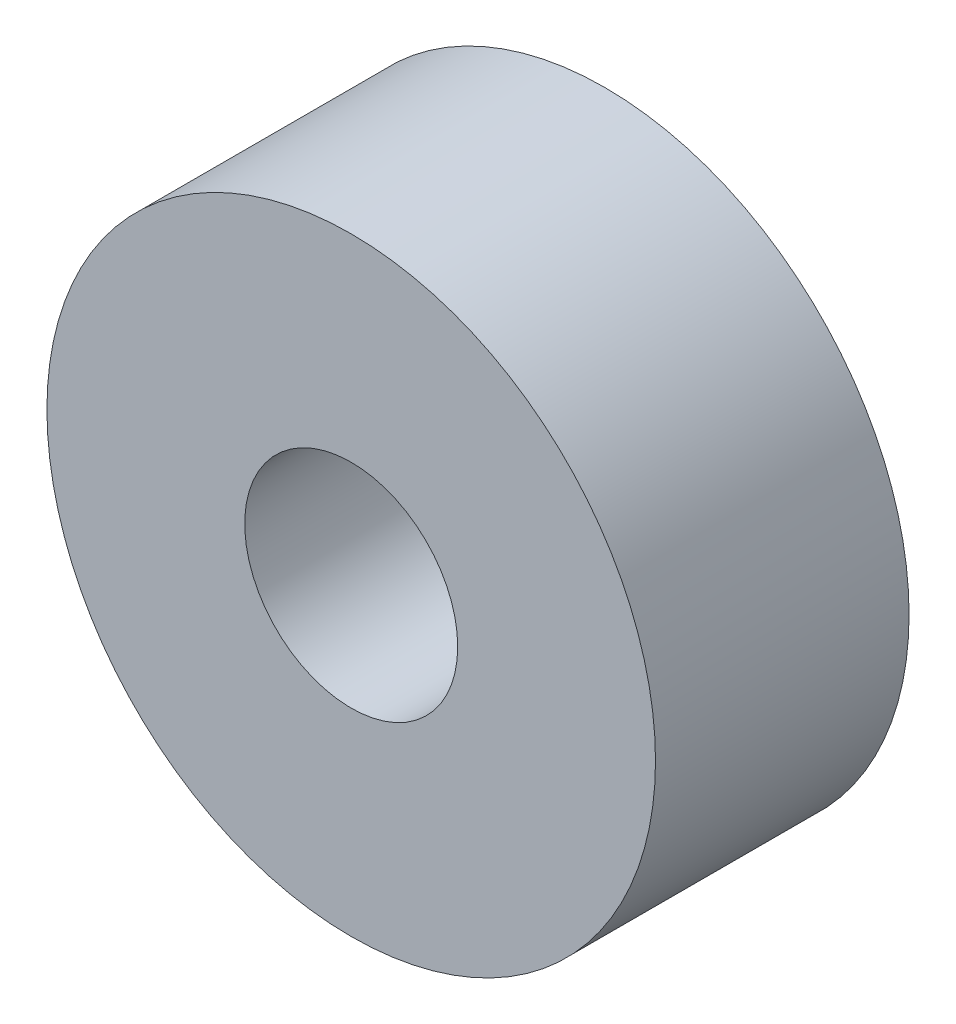
SolidWorks part; units mm, degrees
ref_plane "Front Plane" through (0, 0, 0) normal (0, 0, 1) x (1, 0, 0)
ref_plane "Top Plane" through (0, 0, 0) normal (0, 1, 0) x (1, 0, 0)
ref_plane "Right Plane" through (0, 0, 0) normal (1, 0, 0) x (0, 0, -1)
sketch "Sketch1" plane through (0, 0, 0) normal (0, 0, 1) x (1, 0, 0)
  circle A0 centre (0, 0) radius 6
  circle A1 centre (0, 0) radius 2.1
  dimension "D1" = 12
  dimension "D2" = 4.2
extrude "Boss-Extrude1" add sketch "Sketch1" along normal blind 5
